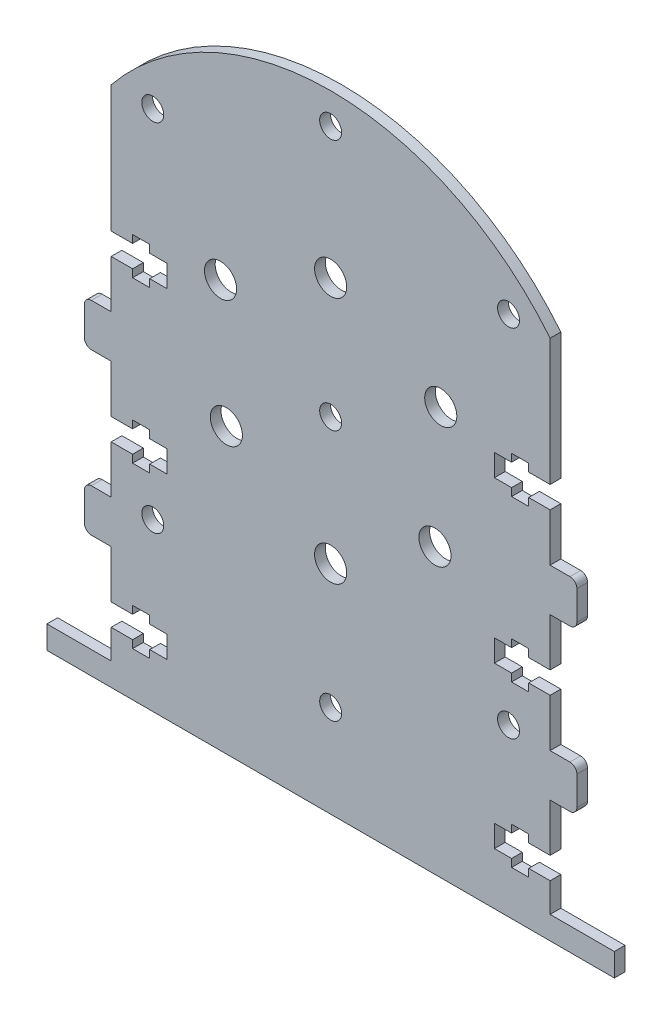
SolidWorks part; units mm, degrees
ref_plane "前视基准面" through (0, 0, 0) normal (0, 0, 1) x (1, 0, 0)
ref_plane "上视基准面" through (0, 0, 0) normal (0, 1, 0) x (1, 0, 0)
ref_plane "右视基准面" through (0, 0, 0) normal (1, 0, 0) x (0, 0, -1)
sketch "草图1" plane through (0, 0, 0) normal (0, 0, 1) x (1, 0, 0)
  line L0 (-14.9625, -1.5035) -> (21.2348, -1.5035) construction
  line L1 (-14.9625, -1.5035) -> (24.3099, -24.1774) construction
  line L2 (-14.9625, -25.2535) -> (-14.9625, -1.5035) construction
  line L3 (26.0375, -61.5035) -> (-55.9625, -61.5035) construction
  line L4 (26.0375, -61.5035) -> (26.0375, 58.4965) construction
  line L5 (26.0375, 58.4965) -> (-55.9625, 58.4965) construction
  line L7 (26.0375, -61.5035) -> (-55.9625, 58.4965) construction
  line L8 (26.0375, 58.4965) -> (-55.9625, -61.5035) construction
  line L9 (-14.9625, -1.5035) -> (-98.8628, 46.9364) construction
  line L10 (-14.9625, -1.5035) -> (68.9378, 46.9364) construction
  line L11 (-58.2638, 23.4965) -> (-55.9625, 23.4965) construction
  line L12 (-55.9625, 23.4965) -> (-55.9625, 8.0465)
  line L13 (-55.9625, 8.0465) -> (-51.9625, 8.0465)
  line L14 (-51.9625, 8.0465) -> (-51.9625, 9.4965)
  line L15 (-51.9625, 9.4965) -> (-48.7625, 9.4965)
  line L16 (-48.7625, 9.4965) -> (-48.7625, 8.0465)
  line L17 (-48.7625, 8.0465) -> (-45.5625, 8.0465)
  line L18 (-45.5625, 8.0465) -> (-45.5625, 3.9465)
  line L19 (-45.5625, 3.9465) -> (-48.7625, 3.9465)
  line L20 (-48.7625, 3.9465) -> (-48.7625, 2.4965)
  line L21 (-48.7625, 2.4965) -> (-51.9625, 2.4965)
  line L22 (-51.9625, 2.4965) -> (-51.9625, 3.9465)
  line L23 (-51.9625, 3.9465) -> (-55.9625, 3.9465)
  line L24 (-55.9625, -5.0035) -> (-60.9625, -5.0035)
  line L25 (-60.9625, -5.0035) -> (-60.9625, -13.0035)
  line L26 (-60.9625, -13.0035) -> (-55.9625, -13.0035)
  line L27 (-60.9625, -9.0035) -> (-58.1553, -9.0035) construction
  line L28 (-51.9625, -21.9535) -> (-55.9625, -21.9535)
  line L29 (-51.9625, -20.5035) -> (-51.9625, -21.9535)
  line L30 (-48.7625, -20.5035) -> (-51.9625, -20.5035)
  line L31 (-48.7625, -21.9535) -> (-48.7625, -20.5035)
  line L32 (-45.5625, -21.9535) -> (-48.7625, -21.9535)
  line L33 (-45.5625, -26.0535) -> (-45.5625, -21.9535)
  line L34 (-48.7625, -26.0535) -> (-45.5625, -26.0535)
  line L35 (-48.7625, -27.5035) -> (-48.7625, -26.0535)
  line L36 (-51.9625, -27.5035) -> (-48.7625, -27.5035)
  line L37 (-51.9625, -26.0535) -> (-51.9625, -27.5035)
  line L38 (-55.9625, -26.0535) -> (-51.9625, -26.0535)
  line L39 (-55.9625, -21.9535) -> (-55.9625, -13.0035)
  line L40 (-45.5625, -24.0035) -> (-48.2625, -24.0035) construction
  line L41 (-55.9625, -43.0035) -> (-60.9625, -43.0035)
  line L42 (-60.9625, -43.0035) -> (-60.9625, -35.0035)
  line L43 (-60.9625, -35.0035) -> (-55.9625, -35.0035)
  line L44 (-60.9625, -39.0035) -> (-57.1747, -39.0035) construction
  line L45 (-45.5625, -54.0035) -> (-48.2625, -54.0035) construction
  line L46 (-55.9625, 3.9465) -> (-55.9625, -5.0035)
  line L47 (-55.9625, -26.0535) -> (-55.9625, -35.0035)
  line L48 (-55.9625, -51.9535) -> (-51.9625, -51.9535)
  line L49 (-51.9625, -51.9535) -> (-51.9625, -50.5035)
  line L50 (-51.9625, -50.5035) -> (-48.7625, -50.5035)
  line L51 (-48.7625, -50.5035) -> (-48.7625, -51.9535)
  line L52 (-48.7625, -51.9535) -> (-45.5625, -51.9535)
  line L53 (-45.5625, -51.9535) -> (-45.5625, -56.0535)
  line L54 (-45.5625, -56.0535) -> (-48.7625, -56.0535)
  line L55 (-48.7625, -56.0535) -> (-48.7625, -57.5035)
  line L56 (-48.7625, -57.5035) -> (-51.9625, -57.5035)
  line L57 (-51.9625, -57.5035) -> (-51.9625, -56.0535)
  line L58 (-51.9625, -56.0535) -> (-55.9625, -56.0535)
  line L59 (-55.9625, -43.0035) -> (-55.9625, -51.9535)
  line L60 (-55.9625, -56.0535) -> (-55.9625, -61.5035)
  line L61 (15.6375, -54.0035) -> (18.3375, -54.0035) construction
  line L62 (31.0375, -39.0035) -> (27.2497, -39.0035) construction
  line L63 (15.6375, -24.0035) -> (18.3375, -24.0035) construction
  line L64 (31.0375, -9.0035) -> (28.2303, -9.0035) construction
  line L65 (26.0375, -43.0035) -> (26.0375, -51.9535)
  line L66 (22.0375, -56.0535) -> (26.0375, -56.0535)
  line L67 (22.0375, -57.5035) -> (22.0375, -56.0535)
  line L68 (18.8375, -57.5035) -> (22.0375, -57.5035)
  line L69 (18.8375, -56.0535) -> (18.8375, -57.5035)
  line L70 (15.6375, -56.0535) -> (18.8375, -56.0535)
  line L71 (15.6375, -51.9535) -> (15.6375, -56.0535)
  line L72 (18.8375, -51.9535) -> (15.6375, -51.9535)
  line L73 (18.8375, -50.5035) -> (18.8375, -51.9535)
  line L74 (22.0375, -50.5035) -> (18.8375, -50.5035)
  line L75 (22.0375, -51.9535) -> (22.0375, -50.5035)
  line L76 (26.0375, -51.9535) -> (22.0375, -51.9535)
  line L77 (26.0375, -26.0535) -> (26.0375, -35.0035)
  line L78 (26.0375, 3.9465) -> (26.0375, -5.0035)
  line L79 (31.0375, -35.0035) -> (26.0375, -35.0035)
  line L80 (31.0375, -43.0035) -> (31.0375, -35.0035)
  line L81 (26.0375, -43.0035) -> (31.0375, -43.0035)
  line L82 (26.0375, -21.9535) -> (26.0375, -13.0035)
  line L83 (26.0375, -26.0535) -> (22.0375, -26.0535)
  line L84 (22.0375, -26.0535) -> (22.0375, -27.5035)
  line L85 (22.0375, -27.5035) -> (18.8375, -27.5035)
  line L86 (18.8375, -27.5035) -> (18.8375, -26.0535)
  line L87 (18.8375, -26.0535) -> (15.6375, -26.0535)
  line L88 (15.6375, -26.0535) -> (15.6375, -21.9535)
  line L89 (15.6375, -21.9535) -> (18.8375, -21.9535)
  line L90 (18.8375, -21.9535) -> (18.8375, -20.5035)
  line L91 (18.8375, -20.5035) -> (22.0375, -20.5035)
  line L92 (22.0375, -20.5035) -> (22.0375, -21.9535)
  line L93 (22.0375, -21.9535) -> (26.0375, -21.9535)
  line L94 (31.0375, -13.0035) -> (26.0375, -13.0035)
  line L95 (31.0375, -5.0035) -> (31.0375, -13.0035)
  line L96 (26.0375, -5.0035) -> (31.0375, -5.0035)
  line L97 (22.0375, 3.9465) -> (26.0375, 3.9465)
  line L98 (22.0375, 2.4965) -> (22.0375, 3.9465)
  line L99 (18.8375, 2.4965) -> (22.0375, 2.4965)
  line L100 (18.8375, 3.9465) -> (18.8375, 2.4965)
  line L101 (15.6375, 3.9465) -> (18.8375, 3.9465)
  line L102 (15.6375, 8.0465) -> (15.6375, 3.9465)
  line L103 (18.8375, 8.0465) -> (15.6375, 8.0465)
  line L104 (18.8375, 9.4965) -> (18.8375, 8.0465)
  line L105 (22.0375, 9.4965) -> (18.8375, 9.4965)
  line L106 (22.0375, 8.0465) -> (22.0375, 9.4965)
  line L107 (26.0375, 8.0465) -> (22.0375, 8.0465)
  line L108 (26.0375, 23.4965) -> (26.0375, 8.0465)
  line L109 (28.3388, 23.4965) -> (26.0375, 23.4965) construction
  line L110 (26.0375, -56.0535) -> (26.0375, -61.5035)
  line L115 (-55.9625, 23.4965) -> (-55.9625, 31.723)
  line L116 (26.0375, 23.4965) -> (26.0375, 31.723)
  line L117 (-45.5625, 5.9965) -> (-55.9625, 5.9965) construction
  line L118 (-67.9625, -65.7919) -> (38.0375, -65.7919)
  line L125 (-55.9625, -61.5035) -> (-67.9625, -61.5035)
  line L126 (-67.9625, -61.5035) -> (-67.9625, -65.7919)
  line L127 (26.0375, -61.5035) -> (38.0375, -61.5035)
  line L128 (38.0375, -61.5035) -> (38.0375, -65.7919)
  circle A0 centre (-14.9625, -1.5035) radius 23.75 construction
  circle A1 centre (-14.9625, -1.5035) radius 22.5 construction
  circle A2 centre (-14.9625, -25.2535) radius 3
  circle A5 centre (4.5231, -12.7535) radius 3
  circle A8 centre (-14.9625, -1.5035) radius 2.05
  circle A15 centre (-14.9625, -1.5035) radius 47 construction
  circle A17 centre (-35.5306, 10.3715) radius 3
  circle A18 centre (-34.4481, -12.7535) radius 3
  circle A19 centre (5.6056, 10.3715) radius 3
  circle A20 centre (-14.9625, 20.9965) radius 3
  circle A21 centre (32.0375, -1.5035) radius 2.05 construction
  circle A22 centre (18.2715, -34.7375) radius 2.05
  circle A23 centre (-14.9625, -48.5035) radius 2.05
  circle A24 centre (-48.1965, -34.7375) radius 2.05
  circle A25 centre (-61.9625, -1.5035) radius 2.05 construction
  circle A26 centre (-48.1965, 31.7305) radius 2.05
  circle A27 centre (-14.9625, 45.4965) radius 2.05
  circle A28 centre (18.2715, 31.7305) radius 2.05
  circle A31 centre (-14.9625, -1.5035) radius 52.7731 construction
  arc A34 (-55.9625, 31.723) -> (26.0375, 31.723) centre (-14.9625, -1.5035) cw
  point P41 (-54.9625, -9.0035)
  point P135 (25.0375, -9.0035)
  dimension "D1" = 47.5
  dimension "D2" = 45
  dimension "D3" = 6
  dimension "D5" = 6
  dimension "D18" = 60
  dimension "D19" = 8
  dimension "D20" = 4.1
  dimension "D21" = 94
  dimension "D22" = 12
  dimension "D23" = 12
  dimension "D4" = 30
  dimension "D6" = 82
  dimension "D8" = 120
  dimension "D9" = 4.1
  dimension "D10" = 3.2
  dimension "D11" = 7
  dimension "D12" = 4
  dimension "D13" = 14
  dimension "D14" = 15
  dimension "D15" = 8
  dimension "D16" = 5
  dimension "D17" = 4
  dimension "D7" = 3
extrude "凸台-拉伸2" add sketch "草图1" along normal blind 2
sketch "草图2" plane through (-55.9625, 0, 0) normal (-1, 0, 0) x (0, 0, 1)
  line L0 (1, -56.0535) -> (1, -51.9535)
  line L1 (2, -56.0535) -> (0, -56.0535) construction
  line L2 (2, -51.9535) -> (0, -51.9535) construction
  circle A0 centre (1, -54.0035) radius 2.05
sketch "草图3" plane through (26.0375, 0, 0) normal (1, 0, 0) x (0, 0, -1)
  line L0 (-1, -51.9535) -> (-1, -56.0535)
  line L1 (-2, -51.9535) -> (0, -51.9535) construction
  line L2 (-2, -56.0535) -> (0, -56.0535) construction
  circle A0 centre (-1, -54.0035) radius 2.05
fillet "圆角1" radius 1.3 8 edges at (-60.9625, -5.0035, 1) (-60.9625, -35.0035, 1) (-60.9625, -13.0035, 1) (-60.9625, -43.0035, 1) (31.0375, -43.0035, 1) (31.0375, -35.0035, 1) (31.0375, -5.0035, 1) (31.0375, -13.0035, 1)
